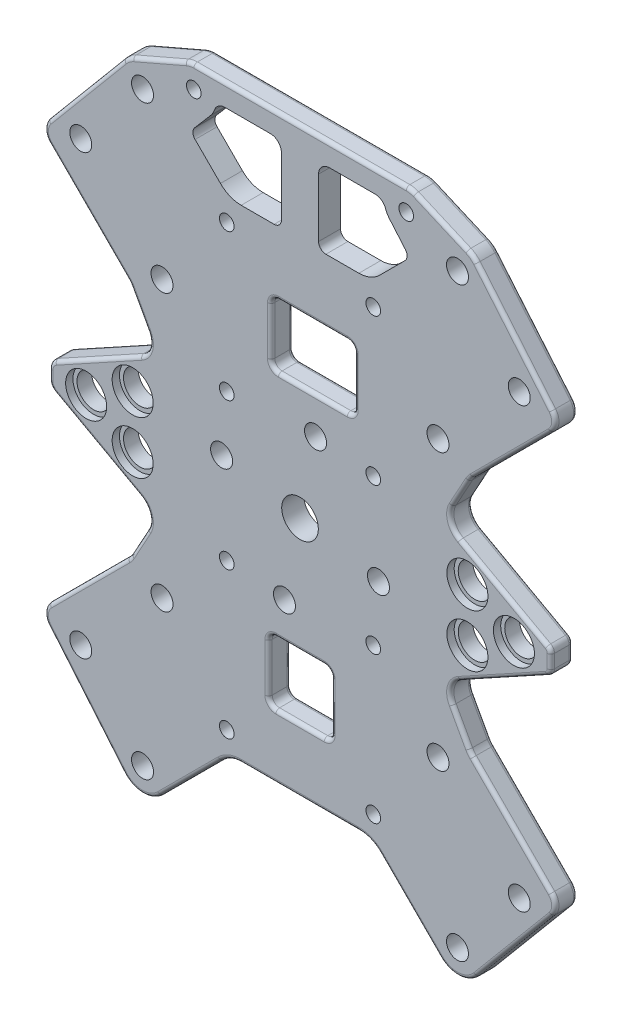
SolidWorks part; units mm, degrees
ref_plane "前视基准面" through (0, 0, 0) normal (0, 0, 1) x (1, 0, 0)
ref_plane "上视基准面" through (0, 0, 0) normal (0, 1, 0) x (1, 0, 0)
ref_plane "右视基准面" through (0, 0, 0) normal (1, 0, 0) x (0, 0, -1)
sketch "草图1" plane through (0, 0, 0) normal (0, 0, 1) x (1, 0, 0)
  line L0 (-19.0958, 42.4042) -> (-10.8632, 34.1716) construction
  line L1 (-8.0348, 33) -> (8.0348, 33) construction
  line L2 (10.8632, 34.1716) -> (19.0958, 42.4042) construction
  line L3 (-10.8632, -34.1716) -> (-19.0958, -42.4042) construction
  line L4 (8.0348, -33) -> (-8.0348, -33) construction
  line L5 (19.0958, -42.4042) -> (10.8632, -34.1716) construction
  line L6 (-19.0958, 42.4042) -> (-10.8632, 34.1716)
  line L7 (-8.0348, 33) -> (8.0348, 33)
  line L8 (10.8632, 34.1716) -> (19.0958, 42.4042)
  line L9 (-10.8632, -34.1716) -> (-19.0958, -42.4042)
  line L10 (8.0348, -33) -> (-8.0348, -33)
  line L11 (19.0958, -42.4042) -> (10.8632, -34.1716)
  line L12 (24.1062, -42.1835) -> (34.3946, -29.9034)
  line L13 (23.2721, -16.201) -> (52.8941, -45.823) construction
  line L14 (40.9735, -22.0509) -> (24.1062, -42.1835) construction
  line L15 (-34.3946, 29.9034) -> (-24.1062, 42.1835)
  line L16 (-82.5161, -75.445) -> (-71.0072, -63.9361) construction
  line L17 (-24.1062, -42.1835) -> (-40.9735, -22.0509) construction
  line L18 (-34.2758, 27.2047) -> (-23.5745, 16.5034)
  line L19 (34.2758, -27.2047) -> (23.5745, -16.5034)
  line L20 (19.6205, -9.552) -> (23.0662, -15.8262)
  line L21 (19.25, -8.1079) -> (19.25, 8.1079)
  line L22 (0, 0) -> (35.9573, 0) construction
  line L23 (19.25, 8.1079) -> (19.25, -8.1079) construction
  line L24 (19.6205, 9.552) -> (23.0662, 15.8262)
  line L25 (34.2758, 27.2047) -> (23.5745, 16.5034)
  line L26 (34.3946, 29.9034) -> (24.1062, 42.1835)
  line L27 (0, 0) -> (0, -57.3498) construction
  line L28 (-19.6205, 9.552) -> (-23.0662, 15.8262)
  line L29 (-19.25, -8.1079) -> (-19.25, 8.1079)
  line L30 (-19.6205, -9.552) -> (-23.0662, -15.8262)
  line L31 (-24.1062, -42.1835) -> (-34.3946, -29.9034)
  line L32 (-34.2758, -27.2047) -> (-23.5745, -16.5034)
  line L33 (7.4463, 16.7071) -> (7.4463, 23.2929) construction
  line L34 (-2.9463, 24.2929) -> (6.4463, 24.2929) construction
  line L35 (-3.9463, 16.7071) -> (-3.9463, 23.2929) construction
  line L36 (-2.9463, 15.7071) -> (6.4463, 15.7071) construction
  line L37 (4.2929, -23.2929) -> (4.2929, -16.7071) construction
  line L38 (-3.2929, -15.7071) -> (3.2929, -15.7071) construction
  line L39 (-4.2929, -23.2929) -> (-4.2929, -16.7071) construction
  line L40 (-3.2929, -24.2929) -> (3.2929, -24.2929) construction
  line L41 (7.4463, 16.7071) -> (7.4463, 23.2929)
  line L42 (-2.9463, 24.2929) -> (6.4463, 24.2929)
  line L43 (-3.9463, 16.7071) -> (-3.9463, 23.2929)
  line L44 (-2.9463, 15.7071) -> (6.4463, 15.7071)
  line L45 (4.2929, -23.2929) -> (4.2929, -16.7071)
  line L46 (-3.2929, -15.7071) -> (3.2929, -15.7071)
  line L47 (-4.2929, -23.2929) -> (-4.2929, -16.7071)
  line L48 (-3.2929, -24.2929) -> (3.2929, -24.2929)
  circle A0 centre (21.5, -40) radius 1.5 construction
  circle A1 centre (21.5, 40) radius 1.5 construction
  circle A2 centre (-21.5, 40) radius 1.5 construction
  circle A3 centre (-21.5, -40) radius 1.5 construction
  circle A4 centre (21.5, -40) radius 1.5
  circle A5 centre (21.5, 40) radius 1.5
  circle A6 centre (-21.5, 40) radius 1.5
  circle A7 centre (-21.5, -40) radius 1.5
  circle A9 centre (-2.1213, -10.7071) radius 1.5
  circle A10 centre (10.7071, -2.1213) radius 1.5
  circle A11 centre (2.1213, 10.7071) radius 1.5
  circle A12 centre (-10.7071, 2.1213) radius 1.5
  circle A13 centre (-18.8388, -18.8388) radius 1.5
  circle A14 centre (-29.9337, -29.9337) radius 1.5
  circle A15 centre (18.8388, -18.8388) radius 1.5
  circle A16 centre (29.9337, -29.9337) radius 1.5
  circle A17 centre (29.9337, 29.9337) radius 1.5
  circle A18 centre (18.8388, 18.8388) radius 1.5
  circle A19 centre (-29.9337, 29.9337) radius 1.5
  circle A20 centre (-18.8388, 18.8388) radius 1.5
  circle A21 centre (-10, -30) radius 1 construction
  circle A22 centre (10, -30) radius 1 construction
  circle A23 centre (10, 30) radius 1 construction
  circle A24 centre (-10, 30) radius 1 construction
  circle A25 centre (0, 0) radius 2.5 construction
  circle A26 centre (-10, 10) radius 1 construction
  circle A27 centre (10, 10) radius 1 construction
  circle A28 centre (10, -10) radius 1 construction
  circle A29 centre (-10, -10) radius 1 construction
  circle A30 centre (-10, -30) radius 1
  circle A31 centre (10, -30) radius 1
  circle A32 centre (10, 30) radius 1
  circle A33 centre (-10, 30) radius 1
  circle A34 centre (0, 0) radius 2.5
  circle A35 centre (-10, 10) radius 1
  circle A36 centre (10, 10) radius 1
  circle A37 centre (10, -10) radius 1
  circle A38 centre (-10, -10) radius 1
  arc A39 (-19.0958, 42.4042) -> (-24.1062, 42.1835) centre (-21.5, 40) ccw construction
  arc A42 (-10.8632, 34.1716) -> (-8.0348, 33) centre (-8.0348, 37) ccw construction
  arc A43 (8.0348, 33) -> (10.8632, 34.1716) centre (8.0348, 37) ccw construction
  arc A44 (24.1062, 42.1835) -> (19.0958, 42.4042) centre (21.5, 40) ccw construction
  arc A45 (19.0958, -42.4042) -> (24.1062, -42.1835) centre (21.5, -40) ccw construction
  arc A46 (-24.1062, -42.1835) -> (-19.0958, -42.4042) centre (-21.5, -40) ccw construction
  arc A47 (-8.0348, -33) -> (-10.8632, -34.1716) centre (-8.0348, -37) ccw construction
  arc A48 (10.8632, -34.1716) -> (8.0348, -33) centre (8.0348, -37) ccw construction
  arc A49 (-19.0958, 42.4042) -> (-24.1062, 42.1835) centre (-21.5, 40) ccw
  arc A50 (-10.8632, 34.1716) -> (-8.0348, 33) centre (-8.0348, 37) ccw
  arc A51 (8.0348, 33) -> (10.8632, 34.1716) centre (8.0348, 37) ccw
  arc A52 (24.1062, 42.1835) -> (19.0958, 42.4042) centre (21.5, 40) ccw
  arc A53 (19.0958, -42.4042) -> (24.1062, -42.1835) centre (21.5, -40) ccw
  arc A54 (-24.1062, -42.1835) -> (-19.0958, -42.4042) centre (-21.5, -40) ccw
  arc A55 (-8.0348, -33) -> (-10.8632, -34.1716) centre (-8.0348, -37) ccw
  arc A56 (10.8632, -34.1716) -> (8.0348, -33) centre (8.0348, -37) ccw
  arc A57 (-34.3946, 29.9034) -> (-34.2758, 27.2047) centre (-32.8616, 28.6189) ccw
  arc A58 (34.3946, -29.9034) -> (34.2758, -27.2047) centre (32.8616, -28.6189) ccw
  arc A59 (19.25, -8.1079) -> (20.1287, -10.2292) centre (22.25, -8.1079) ccw construction
  arc A60 (23.5745, -16.5034) -> (23.0662, -15.8262) centre (25.6958, -14.3821) cw
  arc A61 (19.6205, -9.552) -> (19.25, -8.1079) centre (22.25, -8.1079) cw
  arc A62 (19.6205, 9.552) -> (19.25, 8.1079) centre (22.25, 8.1079) ccw
  arc A63 (23.5745, 16.5034) -> (23.0662, 15.8262) centre (25.6958, 14.3821) ccw
  arc A64 (34.3946, 29.9034) -> (34.2758, 27.2047) centre (32.8616, 28.6189) cw
  arc A65 (-23.5745, 16.5034) -> (-23.0662, 15.8262) centre (-25.6958, 14.3821) cw
  arc A66 (-19.6205, 9.552) -> (-19.25, 8.1079) centre (-22.25, 8.1079) cw
  arc A67 (-19.6205, -9.552) -> (-19.25, -8.1079) centre (-22.25, -8.1079) ccw
  arc A68 (-34.3946, -29.9034) -> (-34.2758, -27.2047) centre (-32.8616, -28.6189) cw
  arc A69 (-23.5745, -16.5034) -> (-23.0662, -15.8262) centre (-25.6958, -14.3821) ccw
  arc A70 (-20.1287, -10.2292) -> (-19.25, -8.1079) centre (-22.25, -8.1079) ccw construction
  arc A71 (6.4463, 15.7071) -> (7.4463, 16.7071) centre (6.4463, 16.7071) ccw construction
  arc A72 (7.4463, 23.2929) -> (6.4463, 24.2929) centre (6.4463, 23.2929) ccw construction
  arc A73 (-2.9463, 24.2929) -> (-3.9463, 23.2929) centre (-2.9463, 23.2929) ccw construction
  arc A74 (-3.9463, 16.7071) -> (-2.9463, 15.7071) centre (-2.9463, 16.7071) ccw construction
  arc A75 (3.2929, -24.2929) -> (4.2929, -23.2929) centre (3.2929, -23.2929) ccw construction
  arc A76 (4.2929, -16.7071) -> (3.2929, -15.7071) centre (3.2929, -16.7071) ccw construction
  arc A77 (-3.2929, -15.7071) -> (-4.2929, -16.7071) centre (-3.2929, -16.7071) ccw construction
  arc A78 (-4.2929, -23.2929) -> (-3.2929, -24.2929) centre (-3.2929, -23.2929) ccw construction
  arc A79 (6.4463, 15.7071) -> (7.4463, 16.7071) centre (6.4463, 16.7071) ccw
  arc A80 (7.4463, 23.2929) -> (6.4463, 24.2929) centre (6.4463, 23.2929) ccw
  arc A81 (-2.9463, 24.2929) -> (-3.9463, 23.2929) centre (-2.9463, 23.2929) ccw
  arc A82 (-3.9463, 16.7071) -> (-2.9463, 15.7071) centre (-2.9463, 16.7071) ccw
  arc A83 (3.2929, -24.2929) -> (4.2929, -23.2929) centre (3.2929, -23.2929) ccw
  arc A84 (4.2929, -16.7071) -> (3.2929, -15.7071) centre (3.2929, -16.7071) ccw
  arc A85 (-3.2929, -15.7071) -> (-4.2929, -16.7071) centre (-3.2929, -16.7071) ccw
  arc A86 (-4.2929, -23.2929) -> (-3.2929, -24.2929) centre (-3.2929, -23.2929) ccw
  point P114 (-35.5707, -28.4996)
  point P119 (35.5707, -28.4996)
  point P126 (23.2721, -16.201)
  point P138 (19.25, 0)
  dimension "D1" = 3
  dimension "D3" = 2
  dimension "D4" = 3
extrude "凸台-拉伸1" add sketch "草图1" along normal blind 3
sketch "草图3" plane through (0, 0, 0) normal (0, 0, 1) x (1, 0, 0)
  line L0 (0, 0) -> (-33.5245, 0) construction
  line L1 (0, 0) -> (0, -21.9912) construction
  line L2 (-21.8086, 8.3476) -> (-33.4733, 1.9275)
  line L4 (-34.25, 0.6134) -> (-34.25, -0.6134)
  line L5 (-23.0662, 15.8262) -> (-19.6205, 9.552) construction
  line L6 (-23.0662, 15.8262) -> (-20.8228, 11.7413)
  line L7 (-23.0662, -15.8262) -> (-20.8228, -11.7413)
  line L8 (-21.8086, -8.3476) -> (-33.4733, -1.9275)
  line L9 (21.8086, -8.3476) -> (33.7322, -1.785)
  line L10 (34.25, 0.9089) -> (34.25, -0.9089)
  line L11 (21.8086, 8.3476) -> (33.7322, 1.785)
  line L12 (23.0662, 15.8262) -> (20.8228, 11.7413)
  line L13 (23.0662, -15.8262) -> (20.8228, -11.7413)
  line L14 (-19.25, 8.1079) -> (-19.25, -8.1079) construction
  arc A1 (-21.8086, 8.3476) -> (-20.8228, 11.7413) centre (-23.0141, 10.5378) ccw
  arc A2 (-23.0662, 15.8262) -> (-17.7686, 1.2072) centre (-22.5808, 7.7327) cw
  arc A3 (-23.0662, -15.8262) -> (-17.7686, -1.2072) centre (-22.5808, -7.7327) ccw
  arc A4 (-21.8086, -8.3476) -> (-20.8228, -11.7413) centre (-23.0141, -10.5378) cw
  arc A5 (21.8086, 8.3476) -> (20.8228, 11.7413) centre (23.0141, 10.5378) cw
  arc A6 (23.0662, 15.8262) -> (18.2967, 0.849) centre (22.5808, 7.7327) ccw
  arc A7 (23.0662, -15.8262) -> (18.2967, -0.849) centre (22.5808, -7.7327) cw
  arc A8 (21.8086, -8.3476) -> (20.8228, -11.7413) centre (23.0141, -10.5378) ccw
  arc A9 (-17.7686, 1.2072) -> (-17.7686, -1.2072) centre (-16.8783, 0) ccw
  arc A10 (-33.4733, -1.9275) -> (-34.25, -0.6134) centre (-32.75, -0.6134) cw
  arc A11 (-33.4733, 1.9275) -> (-34.25, 0.6134) centre (-32.75, 0.6134) ccw
  circle A12 centre (-29.2006, 0) radius 1.25 construction
  circle A13 centre (-29.2006, 0) radius 2.25
  circle A14 centre (-22.85, 3.6) radius 2.25
  circle A15 centre (-22.85, -3.6) radius 2.25
  arc A16 (18.2967, 0.849) -> (18.2967, -0.849) centre (17.7683, 0) cw
  circle A17 centre (22.85, 3.6) radius 2.25
  circle A18 centre (22.85, -3.6) radius 2.25
  circle A19 centre (29.2006, 0) radius 2.25
  arc A20 (33.7322, -1.785) -> (34.25, -0.9089) centre (33.25, -0.9089) ccw
  arc A21 (34.25, 0.9089) -> (33.7322, 1.785) centre (33.25, 0.9089) ccw
  point P20 (-34.25, 0)
  point P41 (-20.1427, 0)
  point P44 (-34.25, -1.5)
  point P47 (-34.25, 1.5)
  point P57 (20.1427, 0)
  point P66 (34.25, -1.5)
  point P69 (34.25, 1.5)
  dimension "D1" = 2.5
  dimension "D4" = 1.5
  dimension "D5" = 1.5
  dimension "D6" = 2.5
  dimension "D7" = 4.5
  dimension "D11" = 1
  dimension "D12" = 1
  dimension "D2" = 3
  dimension "D3" = 15
  dimension "D8" = 3.6
  dimension "D9" = 3.6
  dimension "D10" = 7.3
extrude "凸台-拉伸2" add sketch "草图3" along normal up to surface (3 mm away) up to face at (11, -10, 3)
sketch "草图4" plane through (0, 0, 3) normal (0, 0, 1) x (1, 0, 0)
  circle A0 centre (-22.85, 3.6) radius 2.8
  circle A1 centre (-22.85, 3.6) radius 2.25 construction
  circle A2 centre (-29.2006, 0) radius 2.8
  circle A3 centre (-29.2006, 0) radius 2.25 construction
  circle A4 centre (-22.85, -3.6) radius 2.8
  circle A5 centre (-22.85, -3.6) radius 2.25 construction
  circle A6 centre (22.85, 3.6) radius 2.8
  circle A9 centre (22.85, 3.6) radius 2.25 construction
  circle A10 centre (29.2006, 0) radius 2.8
  circle A11 centre (29.2006, 0) radius 2.25 construction
  circle A12 centre (22.85, -3.6) radius 2.8
  circle A13 centre (22.85, -3.6) radius 2.25 construction
  dimension "D1" = 5.6
extrude "切除-拉伸1" cut sketch "草图4" against normal blind 1
sketch "草图5" plane through (0, 0, 3) normal (0, 0, 1) x (1, 0, 0)
  line L0 (22.8504, 43.1203) -> (15.6915, 46.2184)
  line L1 (-22.8504, 43.1203) -> (-15.6915, 46.2184)
  line L2 (-14.5, 46.4652) -> (14.5, 46.4652)
  line L3 (2.5348, 41.9652) -> (2.5348, 33)
  line L4 (8.0348, 33) -> (-8.0348, 33) construction
  line L5 (-2.5348, 41.9652) -> (-2.5348, 33)
  line L6 (4.0348, 43.4652) -> (10.2574, 43.4652)
  line L7 (-4.0348, 43.4652) -> (-10.2574, 43.4652)
  line L8 (12.2198, 41.5156) -> (14.9795, 38.2879)
  line L9 (19.0958, 42.4042) -> (10.8632, 34.1716) construction
  line L10 (-12.2198, 41.5156) -> (-14.9795, 38.2879)
  line L11 (-10.8632, 34.1716) -> (-19.0958, 42.4042) construction
  line L12 (14.9795, 38.2879) -> (10.8632, 34.1716)
  line L13 (8.0348, 33) -> (2.5348, 33)
  line L14 (-14.9795, 38.2879) -> (-10.8632, 34.1716)
  line L15 (-2.5348, 33) -> (-8.0348, 33)
  line L16 (-19.0958, 42.4042) -> (-13.7575, 33.7041)
  line L17 (-13.7575, 33.7041) -> (0.241, 29.9061)
  line L18 (0.241, 29.9061) -> (12.6118, 33)
  line L19 (12.6118, 33) -> (19.0958, 42.4042)
  circle A0 centre (-14.5, 43.4652) radius 1
  circle A1 centre (14.5, 43.4652) radius 1
  circle A2 centre (-14.5, 43.4652) radius 1 construction
  circle A3 centre (14.5, 43.4652) radius 1 construction
  circle A4 centre (-14.5, 43.4652) radius 3 construction
  circle A5 centre (14.5, 43.4652) radius 3 construction
  arc A7 (24.1062, 42.1835) -> (19.0958, 42.4042) centre (21.5, 40) ccw construction
  arc A8 (-19.0958, 42.4042) -> (-24.1062, 42.1835) centre (-21.5, 40) ccw construction
  arc A9 (14.5, 46.4652) -> (15.6915, 46.2184) centre (14.5, 43.4652) cw
  arc A10 (-14.5, 46.4652) -> (-15.6915, 46.2184) centre (-14.5, 43.4652) ccw
  arc A11 (11.6716, 42.4652) -> (12.2198, 41.5156) centre (14.5, 43.4652) ccw
  arc A12 (-11.6716, 42.4652) -> (-12.2198, 41.5156) centre (-14.5, 43.4652) cw
  arc A13 (10.2574, 43.4652) -> (11.6716, 42.4652) centre (10.2574, 41.9652) cw
  arc A14 (2.5348, 41.9652) -> (4.0348, 43.4652) centre (4.0348, 41.9652) cw
  arc A15 (-2.5348, 41.9652) -> (-4.0348, 43.4652) centre (-4.0348, 41.9652) ccw
  arc A16 (-10.2574, 43.4652) -> (-11.6716, 42.4652) centre (-10.2574, 41.9652) ccw
  arc A17 (22.8504, 43.1203) -> (19.0958, 42.4042) centre (21.5, 40) ccw
  arc A18 (10.8632, 34.1716) -> (8.0348, 33) centre (8.0348, 37) cw
  arc A19 (-10.8632, 34.1716) -> (-8.0348, 33) centre (-8.0348, 37) ccw construction
  arc A20 (-10.8632, 34.1716) -> (-8.0348, 33) centre (-8.0348, 37) ccw
  arc A21 (-22.8504, 43.1203) -> (-19.0958, 42.4042) centre (-21.5, 40) cw
  point P46 (11.5, 43.4652)
  point P53 (-11.5, 43.4652)
  dimension "D1" = 2
  dimension "D2" = 6
  dimension "D5" = 1.5
  dimension "D3" = 5.5
  dimension "D4" = 5.5
extrude "凸台-拉伸3" add sketch "草图5" against normal up to surface (3 mm away) up to face at (0.0083, 0, 0)
fillet "圆角2" radius 1 4 edges at (14.9795, 38.2879, 1.5) (2.5348, 33, 1.5) (-2.5348, 33, 1.5) (-14.9795, 38.2879, 1.5)
fillet "圆角1" radius 0.5 128 edges at (-3.6534, 24, 0) (-3.6534, 24, 3) (1.75, 24.2929, 0) (1.75, 24.2929, 3) (7.1534, 24, 0) (7.1534, 24, 3) (7.4463, 20, 0) (7.4463, 20, 3) (7.1534, 16, 0) (7.1534, 16, 3) (1.75, 15.7071, 0) (1.75, 15.7071, 3) (-3.6534, 16, 0) (-3.6534, 16, 3) (-3.9463, 20, 0) (-3.9463, 20, 3) (0, -15.7071, 0) (0, -15.7071, 3) (4, -16, 0) (4, -16, 3) (4.2929, -20, 0) (4.2929, -20, 3) (4, -24, 0) (4, -24, 3) (0, -24.2929, 0) (0, -24.2929, 3) (-4, -24, 0) (-4, -24, 3) (-4.2929, -20, 0) (-4.2929, -20, 3) (-4, -16, 0) (-4, -16, 3) (21.9445, -13.7837, 3) (21.9445, -13.7837, 0) (23.2963, -16.1828, 0) (23.2963, -16.1828, 3) (28.9251, -21.8541, 0) (28.9251, -21.8541, 3) (34.8596, -28.5309, 0) (34.8596, -28.5309, 3) (29.2504, -36.0434, 0) (29.2504, -36.0434, 3) (21.6496, -43.3967, 0) (21.6496, -43.3967, 3) (14.9795, -38.2879, 0) (14.9795, -38.2879, 3) (9.5656, -33.3045, 0) (9.5656, -33.3045, 3) (0, -33, 0) (0, -33, 3) (-9.5656, -33.3045, 0) (-9.5656, -33.3045, 3) (-14.9795, -38.2879, 0) (-14.9795, -38.2879, 3) (-21.6496, -43.3967, 0) (-21.6496, -43.3967, 3) (-29.2504, -36.0434, 0) (-29.2504, -36.0434, 3) (-34.8596, -28.5309, 0) (-34.8596, -28.5309, 3) (-28.9251, -21.8541, 0) (-28.9251, -21.8541, 3) (-23.2963, -16.1828, 0) (-23.2963, -16.1828, 3) (-21.9445, -13.7837, 3) (-21.9445, -13.7837, 0) (-21.9445, 13.7837, 3) (-21.9445, 13.7837, 0) (-23.2963, 16.1828, 0) (-23.2963, 16.1828, 3) (-28.9251, 21.8541, 0) (-28.9251, 21.8541, 3) (-34.8596, 28.5309, 0) (-34.8596, 28.5309, 3) (-29.2504, 36.0434, 0) (-29.2504, 36.0434, 3) (-23.533, 42.7252, 3) (-23.533, 42.7252, 0) (23.533, 42.7252, 3) (23.533, 42.7252, 0) (29.2504, 36.0434, 0) (29.2504, 36.0434, 3) (34.8596, 28.5309, 0) (34.8596, 28.5309, 3) (28.9251, 21.8541, 0) (28.9251, 21.8541, 3) (23.2963, 16.1828, 0) (23.2963, 16.1828, 3) (21.9445, 13.7837, 3) (21.9445, 13.7837, 0) (-27.641, 5.1376, 3) (-27.641, 5.1376, 0) (-20.6133, 9.8404, 3) (-20.6133, 9.8404, 0) (20.6133, 9.8404, 3) (20.6133, 9.8404, 0) (27.7704, 5.0663, 3) (27.7704, 5.0663, 0) (34.1109, 1.4178, 3) (34.1109, 1.4178, 0) (34.25, 0, 3) (34.25, 0, 0) (34.1109, -1.4178, 3) (34.1109, -1.4178, 0) (27.7704, -5.0663, 3) (27.7704, -5.0663, 0) (20.6133, -9.8404, 3) (20.6133, -9.8404, 0) (-20.6133, -9.8404, 3) (-20.6133, -9.8404, 0) (-27.641, -5.1376, 3) (-27.641, -5.1376, 0) (-34.0413, -1.3766, 3) (-34.0413, -1.3766, 0) (-34.25, 0, 3) (-34.25, 0, 0) (-34.0413, 1.3766, 3) (-34.0413, 1.3766, 0) (-19.2709, 44.6694, 0) (-19.2709, 44.6694, 3) (-15.1084, 46.4028, 0) (-15.1084, 46.4028, 3) (0, 46.4652, 0) (0, 46.4652, 3) (15.1084, 46.4028, 0) (15.1084, 46.4028, 3) (19.2709, 44.6694, 0) (19.2709, 44.6694, 3)
